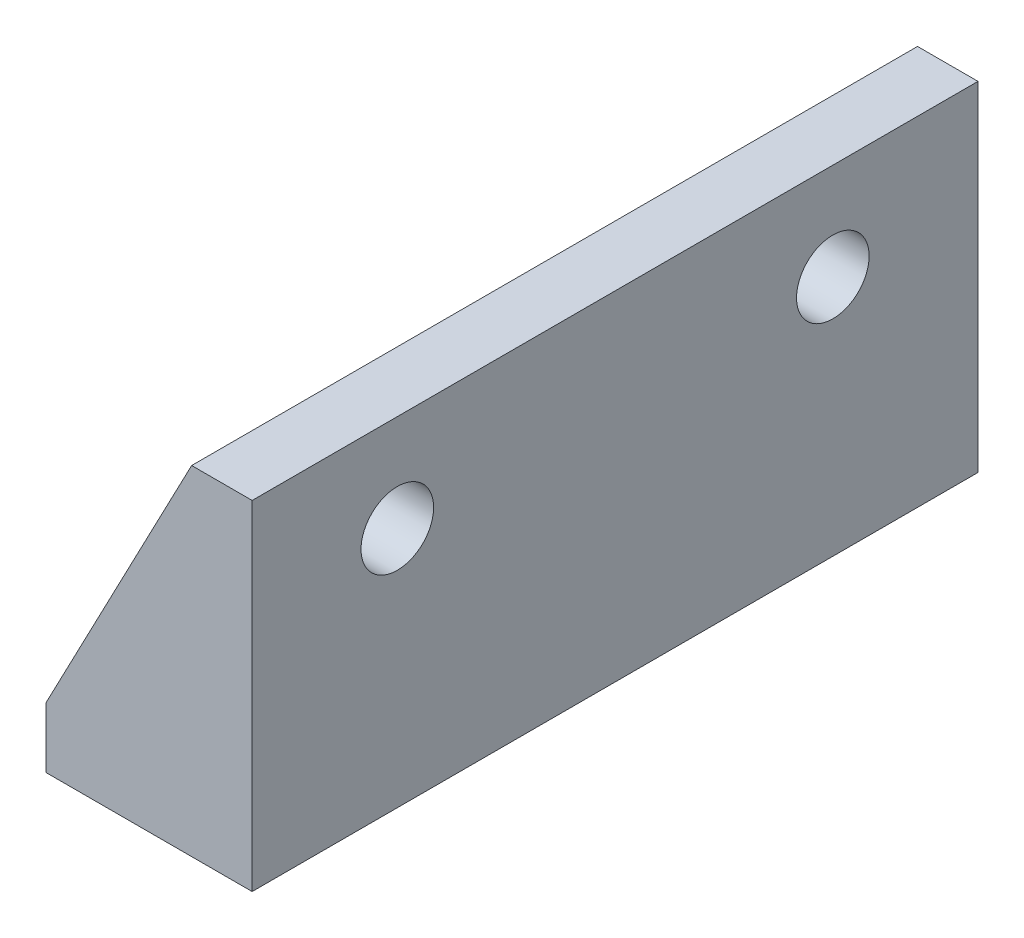
SolidWorks part; units mm, degrees
material "6061-T6 (SS)"
ref_plane "前视基准面" through (0, 0, 0) normal (0, 0, 1) x (1, 0, 0)
ref_plane "上视基准面" through (0, 0, 0) normal (0, 1, 0) x (1, 0, 0)
ref_plane "右视基准面" through (0, 0, 0) normal (1, 0, 0) x (0, 0, -1)
sketch "草图2" plane through (0, 0, 0) normal (0, 0, 1) x (1, 0, 0)
  line L0 (0, 14) -> (0, 0)
  line L1 (0, 0) -> (-8.52, 0)
  point P3 (0, 0)
  dimension "D1" = 14
  dimension "D2" = 8.52
extrude "拉伸-薄壁1" add sketch "草图2" along normal mid plane 30 thin
sketch "草图3" plane through (0, 0, 0) normal (0, -1, 0) x (1, 0, 0)
  line L0 (-16.8209, 0) -> (13.6932, 0) construction
  circle A0 centre (-5.52, 0) radius 1.5
  point P5 (0, 0)
  dimension "D1" = 3
  dimension "D2" = 5.52
extrude "切除-拉伸1" cut sketch "草图3" against normal through all contours A0
sketch "草图4" plane through (0, 0, 15) normal (0, 0, 1) x (1, 0, 0)
  line L0 (-2.5, 14) -> (-8.52, 2.5)
rib "筋1" sketch "草图4" sketch "草图4" thickness 3 extrusion direction parallel to sketch draft on no parameters "D1"=3
mirror "镜向1" about plane through (0, 0, 0) normal (0, 0, 1) of "筋1"
sketch "草图5" plane through (0, 0, 0) normal (1, 0, 0) x (0, 0, -1)
  line L0 (0, 17.0518) -> (0, -3.6474) construction
  line L1 (-15, 14) -> (15, 14) construction
  line L2 (-15, 14) -> (-15, 0) construction
  circle A0 centre (-9, 10) radius 1.5
  circle A1 centre (9, 10) radius 1.5
  dimension "D1" = 3
  dimension "D2" = 4
  dimension "D3" = 6
extrude "切除-拉伸2" cut sketch "草图5" against normal through all
fillet "圆角1" radius 3 2 edges at (-5.51, 2.5, 12) (-5.51, 2.5, -12)
